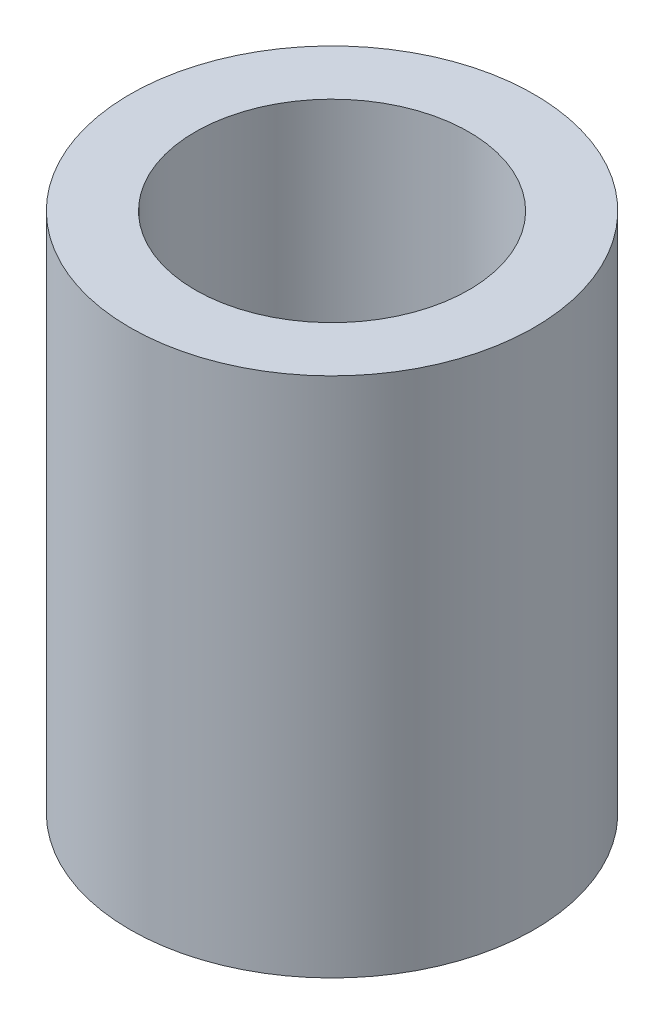
SolidWorks part; units mm, degrees
ref_plane "Front Plane" through (0, 0, 0) normal (0, 0, 1) x (1, 0, 0)
ref_plane "Top Plane" through (0, 0, 0) normal (0, 1, 0) x (1, 0, 0)
ref_plane "Right Plane" through (0, 0, 0) normal (1, 0, 0) x (0, 0, -1)
sketch "Sketch1" plane through (0, 0, 0) normal (0, 1, 0) x (1, 0, 0)
  circle A0 centre (0, 0) radius 3.1
  dimension "D1" = 6.2
extrude "Boss-Extrude1" add sketch "Sketch1" along normal blind 8
sketch "Sketch2" plane through (0, 8, 0) normal (0, 1, 0) x (1, 0, 0)
  circle A0 centre (0, 0) radius 2.1
  dimension "D1" = 4.2
extrude "Cut-Extrude1" cut sketch "Sketch2" against normal through all
